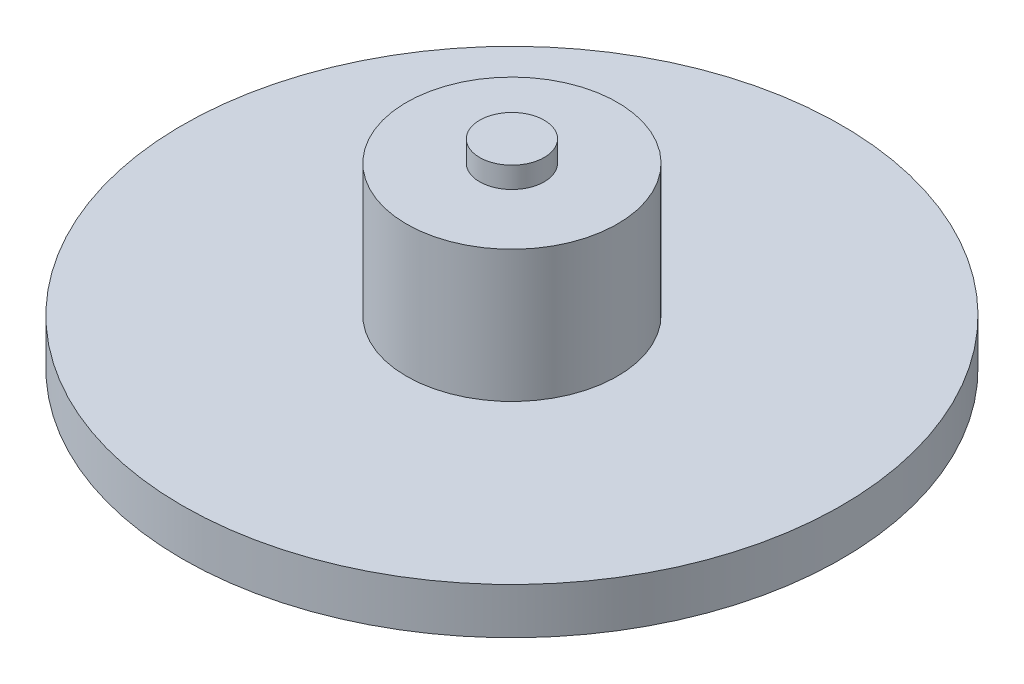
SolidWorks part; units mm, degrees
ref_plane "Front Plane" through (0, 0, 0) normal (0, 0, 1) x (1, 0, 0)
ref_plane "Top Plane" through (0, 0, 0) normal (0, 1, 0) x (1, 0, 0)
ref_plane "Right Plane" through (0, 0, 0) normal (1, 0, 0) x (0, 0, -1)
sketch "Sketch1" plane through (0, 0, 0) normal (0, 1, 0) x (1, 0, 0)
  circle A0 centre (0, 0) radius 25
  dimension "D1" = 50
extrude "Boss-Extrude1" add sketch "Sketch1" along normal blind 3.5
sketch "Sketch2" plane through (0, 3.5, 0) normal (0, 1, 0) x (1, 0, 0)
  circle A0 centre (0, 0) radius 8
  dimension "D1" = 16
extrude "Boss-Extrude2" add sketch "Sketch2" along normal blind 10
sketch "Sketch5" plane through (0, 13.5, 0) normal (0, 1, 0) x (1, 0, 0)
  circle A0 centre (0, 0) radius 2.45
  dimension "D1" = 4.9
extrude "Boss-Extrude3" add sketch "Sketch5" along normal blind 1.6
